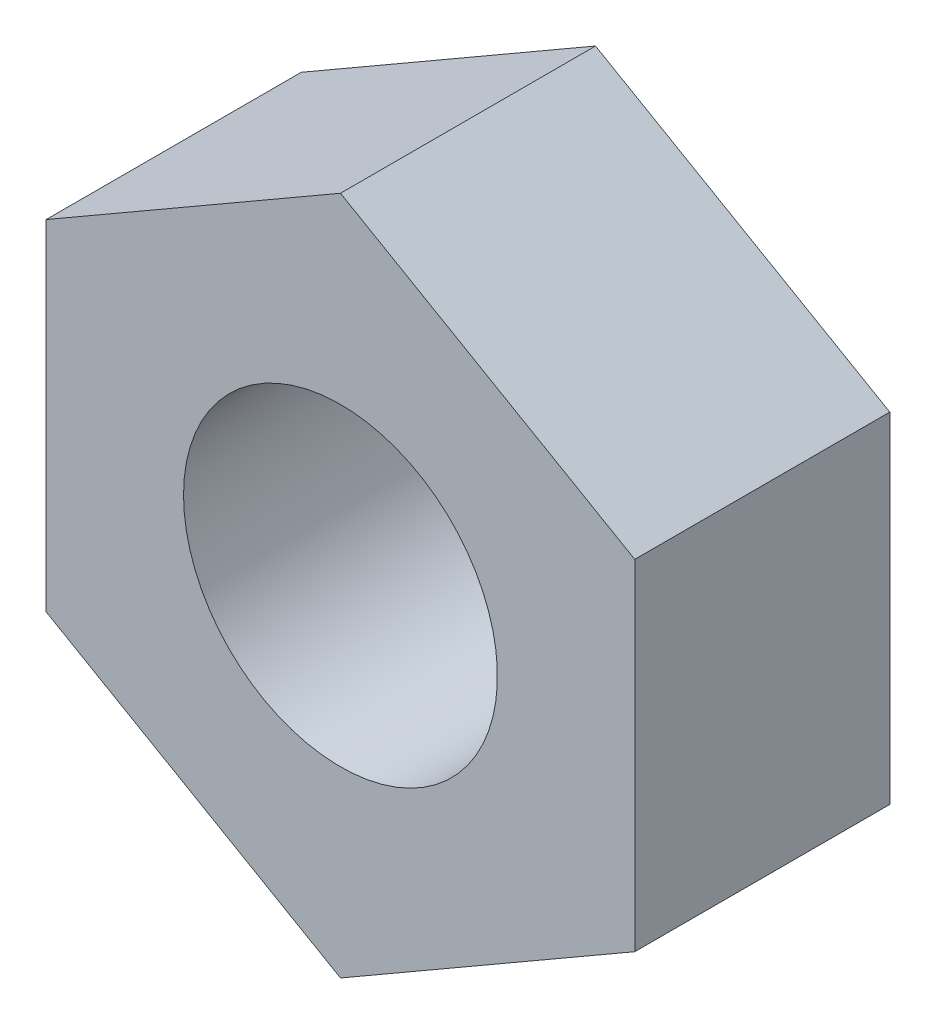
SolidWorks part; units mm, degrees
material "Plain Carbon Steel"
ref_plane "Front Plane" through (0, 0, 0) normal (0, 0, 1) x (1, 0, 0)
ref_plane "Top Plane" through (0, 0, 0) normal (0, 1, 0) x (1, 0, 0)
ref_plane "Right Plane" through (0, 0, 0) normal (1, 0, 0) x (0, 0, -1)
sketch "Sketch1" plane through (0, 0, 0) normal (0, 0, 1) x (1, 0, 0)
  line L1 (15, -8.6603) -> (15, 8.6603)
  line L2 (15, 8.6603) -> (0, 17.3205)
  line L3 (0, 17.3205) -> (-15, 8.6603)
  line L4 (-15, 8.6603) -> (-15, -8.6603)
  line L5 (-15, -8.6603) -> (0, -17.3205)
  line L6 (0, -17.3205) -> (15, -8.6603)
  circle A0 centre (0, 0) radius 8
  circle A1 centre (0, 0) radius 15 construction
  point P3 (-12.7914, 5.3272)
  point P11 (0, 13.8564)
  dimension "D1" = 16
  dimension "D2" = 30
extrude "Boss-Extrude1" add sketch "Sketch1" along normal blind 13
